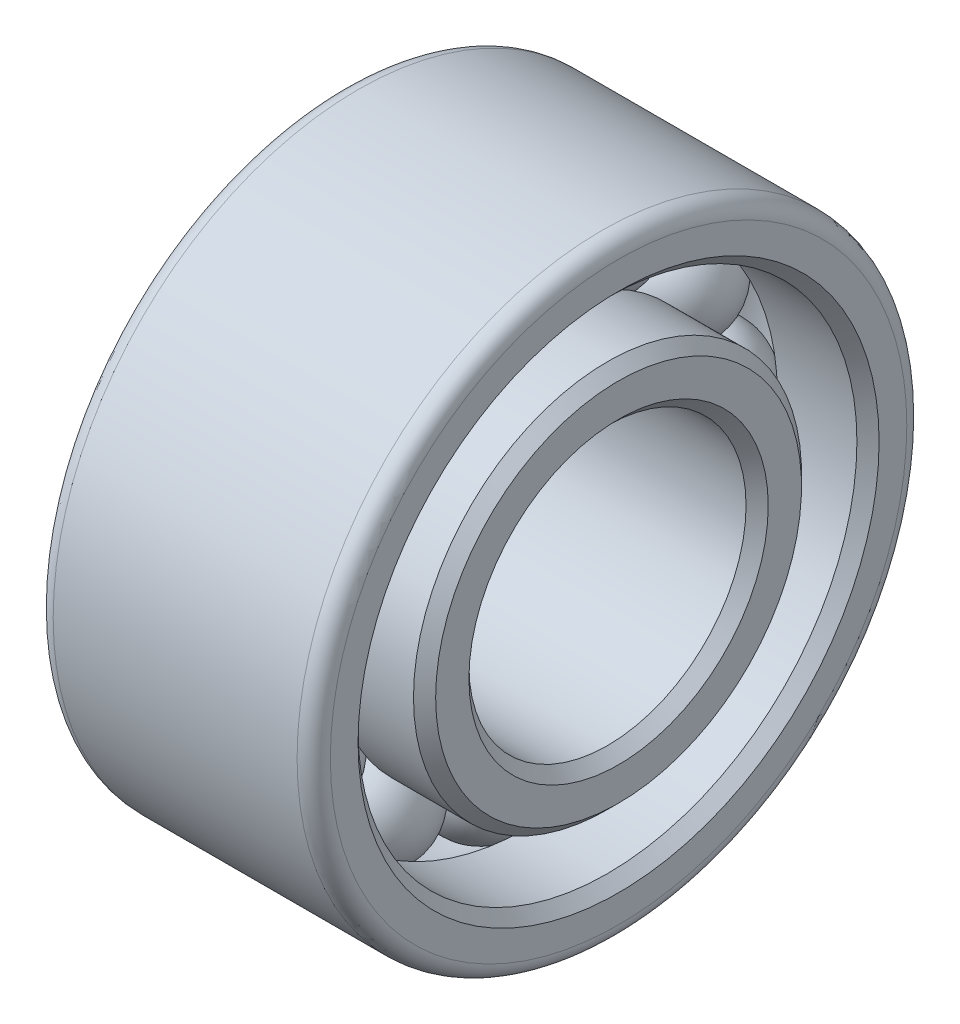
SolidWorks part; units mm, degrees
material "1023 Листовая углеродистая сталь (SS)"
ref_plane "Спереди" through (0, 0, 0) normal (0, 0, 1) x (1, 0, 0)
ref_plane "Сверху" through (0, 0, 0) normal (0, 1, 0) x (1, 0, 0)
ref_plane "Справа" through (0, 0, 0) normal (1, 0, 0) x (0, 0, -1)
sketch "Эскиз1" plane through (0, 0, 0) normal (0, 0, 1) x (1, 0, 0)
  line L0 (-1.0669, -2.5) -> (5.2077, -2.5) construction
  line L1 (0, 0) -> (5, 0)
  line L2 (0, 0) -> (0, 1)
  line L3 (0, 2) -> (1.634, 2)
  line L4 (5, 0) -> (5, 1)
  line L5 (5, 1) -> (3.366, 1)
  line L6 (0, 2) -> (0, 3)
  line L7 (0, 3) -> (5, 3)
  line L8 (5, 2) -> (5, 3)
  line L9 (3.366, 2) -> (5, 2)
  line L10 (1.634, 1) -> (0, 1)
  arc A0 (1.634, 1) -> (3.366, 1) centre (2.5, 1.5) ccw
  arc A1 (3.366, 2) -> (1.634, 2) centre (2.5, 1.5) ccw
  dimension "D7" = 5
  dimension "D2" = 2
  dimension "D8" = 0.5
  dimension "D1" = 2.5
  dimension "D3" = 1
  dimension "D4" = 5
  dimension "D5" = 1
  dimension "D6" = 5.5
revolve "Повернуть1" add sketch "Эскиз1" angle 360 about L0
sketch "Эскиз2" plane through (0, 0, 0) normal (0, 0, 1) x (1, 0, 0)
  line L0 (2.5, 2.5) -> (2.5, 0.5) construction
  line L1 (2.5, 2.5) -> (2.5, 0.5)
  line L2 (5, 3) -> (0, 3) construction
  line L3 (0, 3) -> (0, -8) construction
  arc A0 (2.5, 2.5) -> (2.5, 0.5) centre (2.5, 1.5) ccw
  dimension "D1" = 1
  dimension "D2" = 1.5
  dimension "D3" = 2.5
revolve "Повернуть2" add sketch "Эскиз2" angle 360 about L0
pattern_circular "Круговой массив5" count 12 over 360 about axis through (0, -2.5, 0) along (1, 0, 0) of bodies 105
fillet "Скругление1" radius 0.3 2 edges at (5, -2.5, 5.5) (0, -2.5, 5.5)
chamfer "Фаска1" distance 0.2 angle 45 2 edges at (0, -2.5, 2.5) (5, -2.5, 2.5)
chamfer "Фаска2" distance 0.2 angle 45 2 edges at (5, -2.5, 3.5) (0, -2.5, 3.5)
chamfer "Фаска3" distance 0.2 angle 45 2 edges at (0, -2.5, 4.5) (5, -2.5, 4.5)
ref_plane "Plane1" through (2.5, 0, 0) normal (1, 0, 0) x (0, 0, -1)
sketch "Sketch1" plane through (2.5, 0, 0) normal (1, 0, 0) x (0, 0, -1)
  point P0 (0, -2.5)
